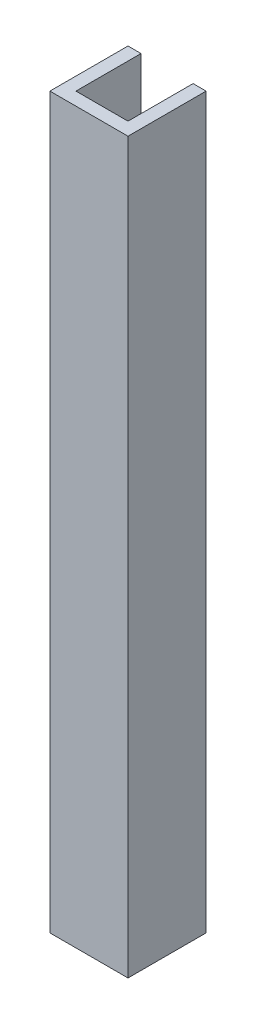
SolidWorks part; units mm, degrees
ref_plane "Front" through (0, 0, 0) normal (0, 0, 1) x (1, 0, 0)
ref_plane "Top" through (0, 0, 0) normal (0, 1, 0) x (1, 0, 0)
ref_plane "Right" through (0, 0, 0) normal (1, 0, 0) x (0, 0, -1)
sketch "Sketch1" plane through (0, 0, 0) normal (0, 1, 0) x (1, 0, 0)
  line L0 (0, 0) -> (19.05, 0)
  line L1 (0, 0) -> (0, 19.05)
  line L2 (0, 19.05) -> (3.175, 19.05)
  line L3 (3.175, 19.05) -> (3.175, 3.175)
  line L4 (3.175, 3.175) -> (15.875, 3.175)
  line L5 (15.875, 3.175) -> (15.875, 19.05)
  line L6 (15.875, 19.05) -> (19.05, 19.05)
  line L7 (19.05, 19.05) -> (19.05, 0)
  dimension "D1" = 19.05
  dimension "D2" = 19.05
  dimension "D3" = 3.175
  dimension "D4" = 15.875
  dimension "D5" = 12.7
extrude "Boss-Extrude1" add sketch "Sketch1" along normal blind 177.8
